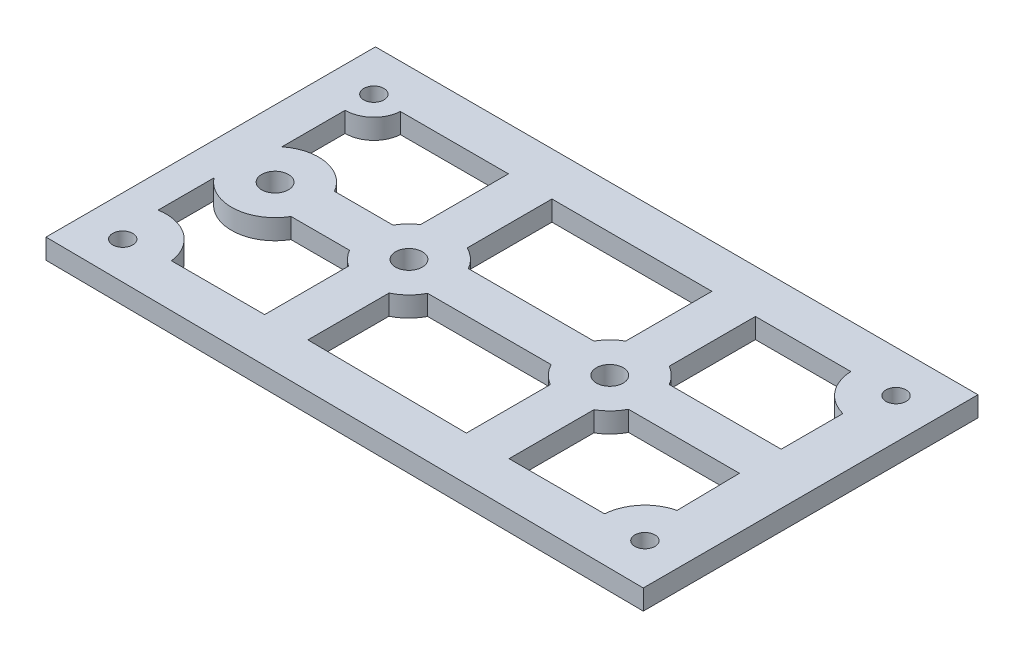
SolidWorks part; units mm, degrees
ref_plane "Front Plane" through (0, 0, 0) normal (0, 0, 1) x (1, 0, 0)
ref_plane "Top Plane" through (0, 0, 0) normal (0, 1, 0) x (1, 0, 0)
ref_plane "Right Plane" through (0, 0, 0) normal (1, 0, 0) x (0, 0, -1)
sketch "Sketch1" plane through (0, 0, 0) normal (0, 1, 0) x (1, 0, 0)
  line L0 (-34.4605, 15.6278) -> (-18.3177, 15.6278)
  line L4 (45.3235, -27.8722) -> (45.3235, 22.1278)
  line L5 (-44.6765, 22.1278) -> (-44.6765, -27.0877)
  line L6 (-44.6765, 22.1278) -> (45.3235, 22.1278)
  line L11 (45.3235, -27.8722) -> (-44.6765, -27.0877)
  line L12 (0.3235, 22.5) -> (0.3235, -22.5) construction
  line L13 (-36.6765, -2.8722) -> (45.3235, -2.8722) construction
  line L15 (-38.7356, 2.2046) -> (-38.7356, 11.6613)
  line L16 (-14.6765, 3.6278) -> (-14.6765, -4.8722) construction
  line L17 (-11.8177, 15.6278) -> (-11.8177, 2.9654)
  line L18 (-18.3177, 15.6278) -> (-18.3177, 2.5122)
  line L19 (-9.0473, 0.3778) -> (9.6943, 0.3778)
  line L20 (-8.9048, -5.8617) -> (9.5503, -5.8589)
  line L21 (-18.3177, -8.2566) -> (-18.3177, -20.7845)
  line L22 (-11.8177, -8.7098) -> (-11.8177, -20.833)
  line L24 (18.5735, 15.6278) -> (18.5735, 2.757)
  line L25 (18.5735, -8.5014) -> (18.5734, -21.1722)
  line L27 (21.0976, -5.8572) -> (37.6698, -5.8547)
  line L28 (45.3235, -27.8722) -> (45.3235, 22.1278)
  line L29 (12.0735, 15.6278) -> (12.0735, 2.757)
  line L30 (-34.2684, -2.3388) -> (-39.792, -6.8824)
  line L34 (-11.8177, 15.6278) -> (12.0735, 15.6278)
  line L36 (-11.8177, -20.833) -> (12.0735, -21.0489)
  line L39 (20.9527, 0.3778) -> (37.6729, 0.3778)
  line L40 (-29.0473, 0.3778) -> (-20.3057, 0.3778)
  line L41 (-29.0473, -6.1222) -> (-20.3057, -6.1222)
  line L43 (37.6729, 0.3778) -> (37.6729, 9.5978)
  line L45 (18.5735, 15.6278) -> (32.8286, 15.6278)
  line L46 (37.6698, -5.8547) -> (37.8086, -15.3081)
  line L47 (32.8396, -21.1722) -> (18.5734, -21.1722)
  line L48 (-39.792, -6.8824) -> (-39.792, -15.2255)
  line L49 (-32.2316, -20.7845) -> (-18.3177, -20.7845)
  line L50 (12.0735, -8.5014) -> (12.0735, -21.0489)
  line L51 (18.5734, -21.1076) -> (22.0734, -21.1392)
  circle A2 centre (-14.6765, -2.8722) radius 2
  circle A3 centre (-34.6765, -2.8722) radius 2
  circle A4 centre (15.3235, -2.8722) radius 2
  arc A6 (-39.792, -6.8824) -> (-29.0473, -6.1222) centre (-34.6765, -2.8722) ccw
  arc A7 (-11.8177, -8.7098) -> (-8.9048, -5.8617) centre (-14.6765, -2.8722) ccw
  arc A8 (12.0735, -8.5014) -> (9.5503, -5.8589) centre (15.3235, -2.8722) cw
  circle A9 centre (-38.6765, 15.8847) radius 1.5
  circle A11 centre (-38.6765, -21.6291) radius 1.5
  circle A13 centre (39.3235, 15.8847) radius 1.5
  circle A15 centre (39.3235, -21.6291) radius 1.5
  arc A17 (9.6943, 0.3778) -> (12.0735, 2.757) centre (15.3235, -2.8722) cw
  arc A18 (18.5735, 2.757) -> (20.9527, 0.3778) centre (15.3235, -2.8722) cw
  arc A19 (-9.0473, 0.3778) -> (-11.8177, 2.9654) centre (-14.6765, -2.8722) ccw
  arc A20 (-18.3177, 2.5122) -> (-20.3057, 0.3778) centre (-14.6765, -2.8722) ccw
  arc A21 (-20.3057, -6.1222) -> (-18.3177, -8.2566) centre (-14.6765, -2.8722) ccw
  arc A22 (-29.0473, 0.3778) -> (-38.7356, 2.2046) centre (-34.6765, -2.8722) ccw
  arc A23 (21.0976, -5.8572) -> (18.5735, -8.5014) centre (15.3235, -2.8722) cw
  arc A25 (-38.7356, 11.6613) -> (-34.4605, 15.6278) centre (-38.6765, 15.8847) ccw
  arc A26 (37.8086, -15.3081) -> (32.8396, -21.1722) centre (39.3235, -21.6291) ccw
  arc A27 (37.6729, 9.5978) -> (32.8286, 15.6278) centre (39.3235, 15.8847) cw
  arc A28 (-32.2316, -20.7845) -> (-39.792, -15.2255) centre (-38.6765, -21.6291) ccw
  point P0 (0, 0)
  point P6 (0, 0)
  dimension "D2" = 30
  dimension "D3" = 4
  dimension "D4" = 4
  dimension "D5" = 20
  dimension "D6" = 4
  dimension "D7" = 30
  dimension "D9" = 6.5
  dimension "D12" = 6.5
  dimension "D13" = 13
  dimension "D15" = 3
  dimension "D11" = 13
  dimension "D10" = 13
  dimension "D8" = 6.5
  dimension "D17" = 6
  dimension "D19" = 50
extrude "Boss-Extrude1" add sketch "Sketch1" along normal blind 3
